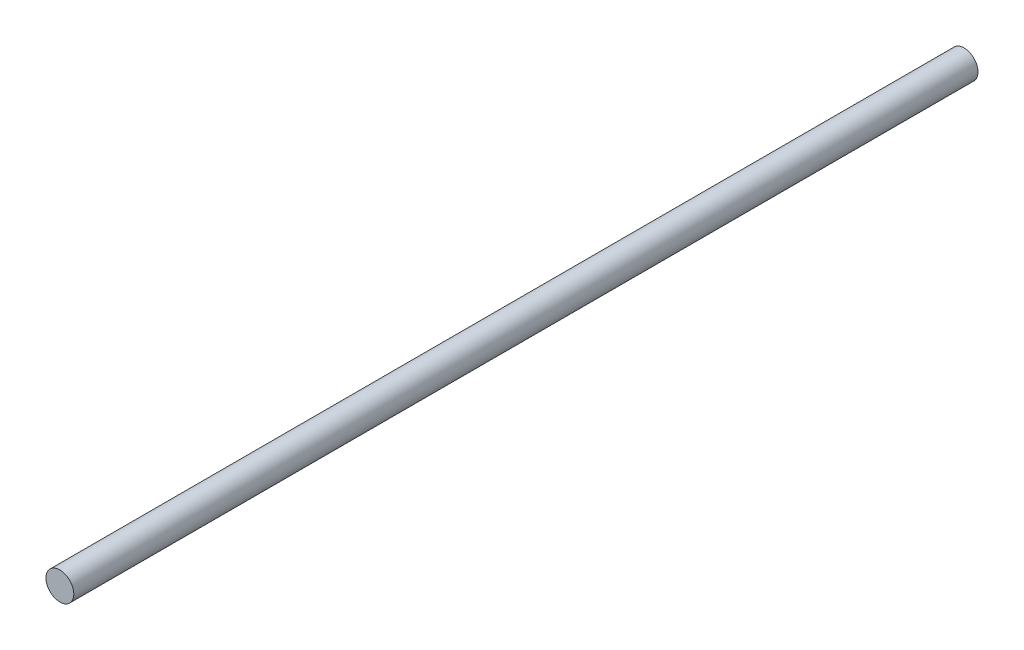
SolidWorks part; units mm, degrees
ref_plane "Plano frontal" through (0, 0, 0) normal (0, 0, 1) x (1, 0, 0)
ref_plane "Plano superior" through (0, 0, 0) normal (0, 1, 0) x (1, 0, 0)
ref_plane "Plano direito" through (0, 0, 0) normal (1, 0, 0) x (0, 0, -1)
sketch "Esboço1" plane through (0, 0, 0) normal (0, 0, 1) x (1, 0, 0)
  circle A0 centre (0, 0) radius 4
  dimension "D1" = 8
extrude "Ressalto-extrusão1" add sketch "Esboço1" along normal mid plane 260
sketch "Esboço4" plane through (0, 0, 130) normal (0, 0, 1) x (1, 0, 0)
  circle A0 centre (0, 0) radius 1.7627
